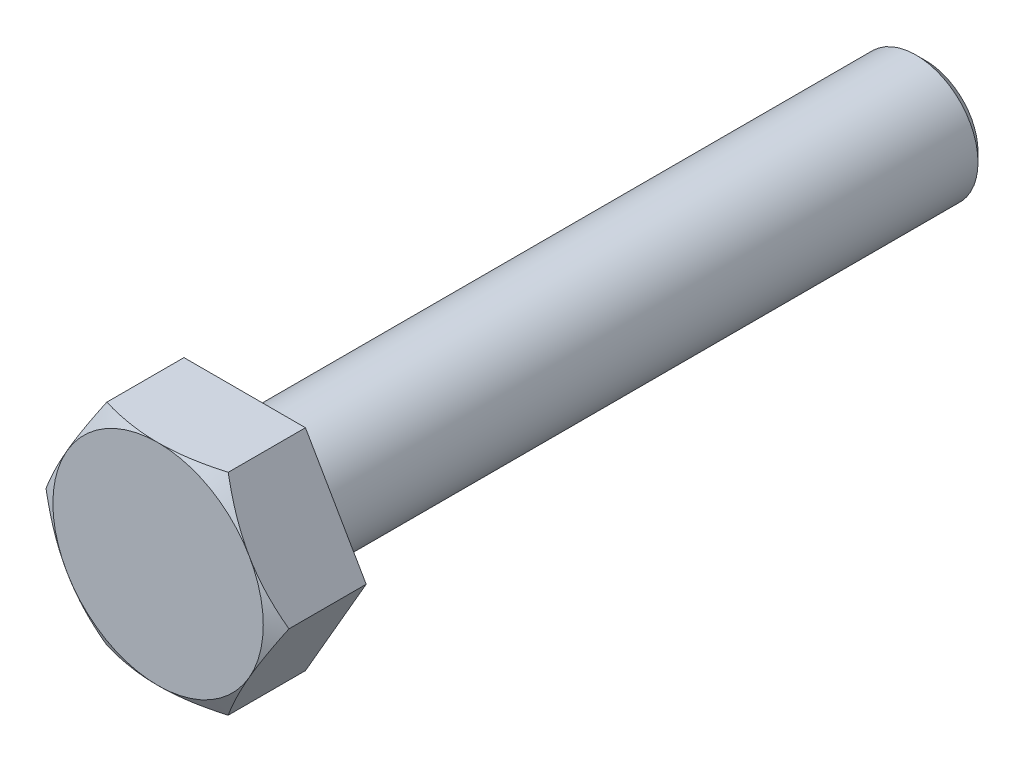
SolidWorks part; units mm, degrees
material "STEEL, GRADE 8.8"
ref_plane "Front Plane" through (0, 0, 0) normal (0, 0, 1) x (1, 0, 0)
ref_plane "Top Plane" through (0, 0, 0) normal (0, 1, 0) x (1, 0, 0)
ref_plane "Right Plane" through (0, 0, 0) normal (1, 0, 0) x (0, 0, -1)
sketch "Sketch1" plane through (0, 0, 0) normal (0, 0, 1) x (1, 0, 0)
  line L1 (9.815, 0) -> (4.9075, 8.5)
  line L2 (4.9075, 8.5) -> (-4.9075, 8.5)
  line L3 (-4.9075, 8.5) -> (-9.815, 0)
  line L4 (-9.815, 0) -> (-4.9075, -8.5)
  line L5 (-4.9075, -8.5) -> (4.9075, -8.5)
  line L6 (4.9075, -8.5) -> (9.815, 0)
  circle A0 centre (0, 0) radius 8.5 construction
  dimension "D1" = 17
extrude "Boss-Extrude1" add sketch "Sketch1" along normal blind 7
sketch "Sketch2" plane through (0, 0, 0) normal (1, 0, 0) x (0, 0, -1)
  line L0 (-7, 8.5) -> (-7, 13.5)
  line L1 (-7, 13.5) -> (-4.1132, 13.5)
  line L2 (-4.1132, 13.5) -> (-7, 8.5)
  line L3 (-7, 0) -> (0, 0) construction
  dimension "D1" = 30
  dimension "D2" = 5
revolve "Cut-Revolve1" cut sketch "Sketch2" angle 360 mid plane about L3
sketch "Sketch3" plane through (0, 0, 0) normal (0, 0, -1) x (-1, 0, 0)
  circle A0 centre (0, 0) radius 5
  dimension "D1" = 10
extrude "Boss-Extrude2" add sketch "Sketch3" along normal blind 55
cosmetic thread "Cosmetic Thread1" parameters "D1"=26, "D2"=8.619
chamfer "Chamfer1" distance 0.75 angle 45 1 edges at (-5, 0, -55)
